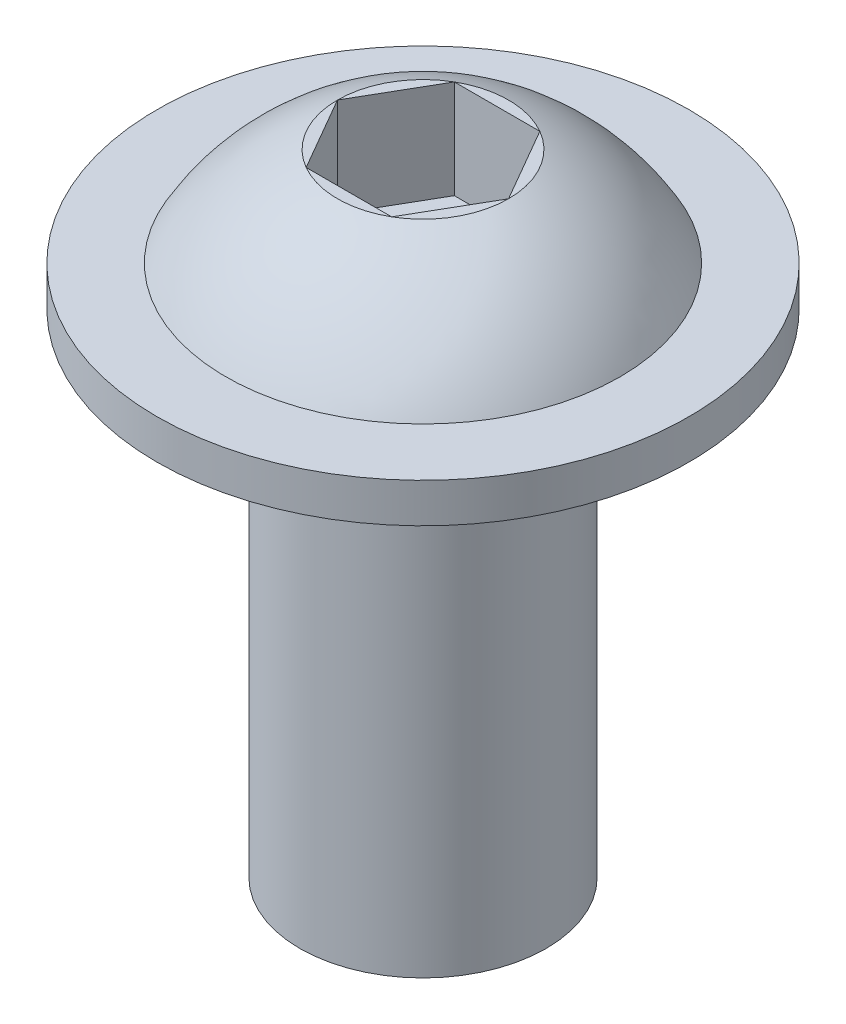
SolidWorks part; units mm, degrees
ref_plane "Front"
ref_plane "Top" through (0, 0, 0) normal (0, 1, 0) x (1, 0, 0)
ref_plane "Right" through (0, 0, 0) normal (1, 0, 0) x (0, 0, -1)
sketch "Sketch1" plane through (0, 0, 0) normal (0, 0, 1) x (1, 0, 0)
  line L0 (0, 0) -> (3.9688, 0)
  line L1 (3.9688, 0) -> (3.9688, 15.875)
  line L2 (3.9688, 15.875) -> (8.5725, 15.875)
  line L3 (8.5725, 15.875) -> (8.5725, 17.145)
  line L4 (8.5725, 17.145) -> (6.35, 17.145)
  line L5 (0, 0) -> (0, 20.32)
  line L6 (0, 0) -> (0, 30.7805) construction
  line L8 (2.757, 20.32) -> (0, 20.32)
  arc A0 (6.35, 17.145) -> (2.757, 20.32) centre (0, 13.5795) ccw
  dimension "MajorDia" = 7.9375
  dimension "Length" = 15.875
  dimension "FlangeThick" = 1.27
  dimension "FlangeDiam" = 17.145
  dimension "HeadDiam" = 12.7
  dimension "HeadHeight" = 4.445
  dimension "D2" = 5.5139
revolve "Screw revolve" add sketch "Sketch1" angle 360 about L6
sketch "Sketch2" plane through (0, 20.32, 0) normal (0, 1, 0) x (-1, 0, 0)
  line L1 (-2.757, 0) -> (-1.3785, -2.3876)
  line L2 (-1.3785, -2.3876) -> (1.3785, -2.3876)
  line L3 (1.3785, -2.3876) -> (2.757, 0)
  line L4 (2.757, 0) -> (1.3785, 2.3876)
  line L5 (1.3785, 2.3876) -> (-1.3785, 2.3876)
  line L6 (-1.3785, 2.3876) -> (-2.757, 0)
  circle A0 centre (0, 0) radius 2.3876 construction
  dimension "HexWidth" = 4.7752
  dimension "D1" = 5.5139
extrude "Hex Cut" cut sketch "Sketch2" against normal blind 3.175
equation "\"D2@Sketch1\" = \"D1@Sketch2\""
